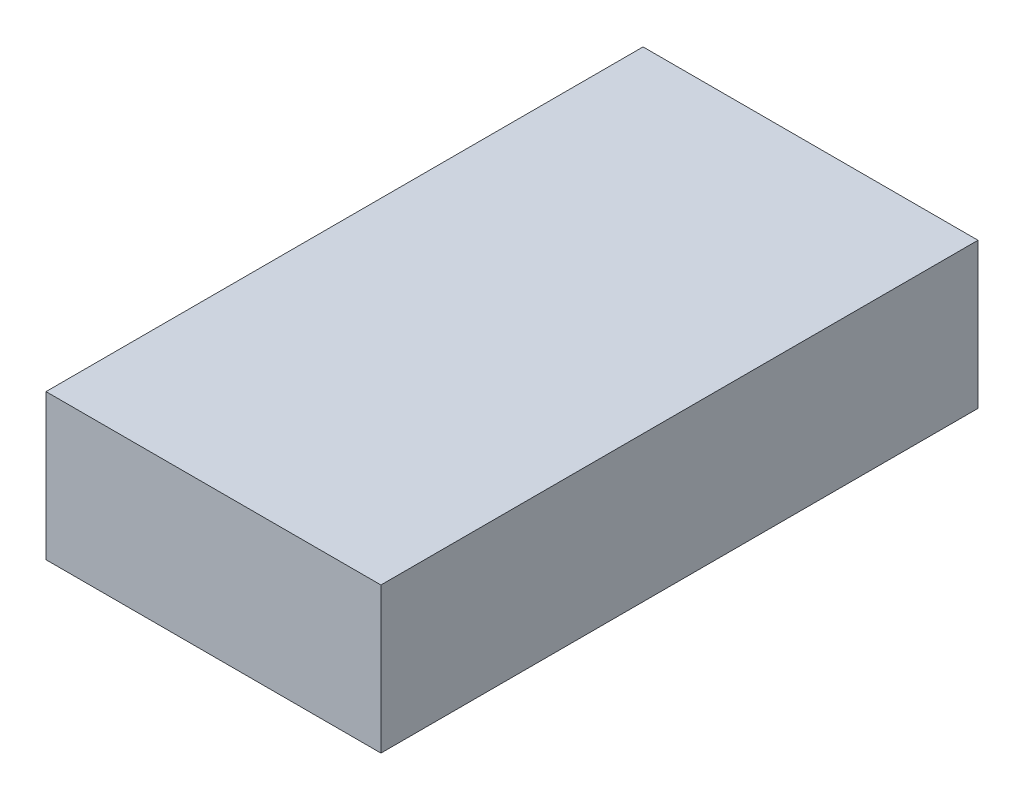
SolidWorks part; units mm, degrees
material "Copper"
ref_plane "Front Plane" through (0, 0, 0) normal (0, 0, 1) x (1, 0, 0)
ref_plane "Top Plane" through (0, 0, 0) normal (0, 1, 0) x (1, 0, 0)
ref_plane "Right Plane" through (0, 0, 0) normal (1, 0, 0) x (0, 0, -1)
sketch "Sketch1" plane through (0, 0, 0) normal (0, 0, 1) x (1, 0, 0)
  line L1 (0, 0) -> (115, 0)
  line L2 (0, 0) -> (0, 50)
  line L3 (0, 50) -> (115, 50)
  line L4 (115, 0) -> (115, 50)
  dimension "D1" = 50
  dimension "D2" = 115
extrude "Boss-Extrude1" add sketch "Sketch1" along normal blind 205
sketch "Sketch2" plane through (0, 0, 0) normal (0, -1, 0) x (1, 0, 0)
  line L0 (9.75, 177.5) -> (104.3481, 177.5) construction
  line L1 (0, 205) -> (115, 205) construction
  line L2 (8.0003, 9.5) -> (104.3481, 9.5) construction
  line L3 (0, 0) -> (115, 0) construction
  line L4 (9.75, 179.5) -> (9.75, 175.5) construction
  line L5 (11.75, 179.5) -> (11.75, 175.5)
  line L6 (7.75, 179.5) -> (7.75, 175.5)
  line L7 (0, 205) -> (0, 0) construction
  line L8 (57.5, 0) -> (57.5, 205) construction
  line L9 (71.2818, 177.5) -> (71.2818, 9.5) construction
  line L11 (105.25, 179.5) -> (105.25, 175.5) construction
  line L12 (103.25, 179.5) -> (103.25, 175.5)
  line L13 (107.25, 179.5) -> (107.25, 175.5)
  line L14 (71.2818, 93.5) -> (7.75, 93.5) construction
  line L15 (9.75, 7.5) -> (9.75, 11.5) construction
  line L16 (11.75, 7.5) -> (11.75, 11.5)
  line L17 (7.75, 7.5) -> (7.75, 11.5)
  line L18 (105.25, 7.5) -> (105.25, 11.5) construction
  line L19 (103.25, 7.5) -> (103.25, 11.5)
  line L20 (107.25, 7.5) -> (107.25, 11.5)
  arc A0 (11.75, 179.5) -> (7.75, 179.5) centre (9.75, 179.5) ccw
  arc A1 (7.75, 175.5) -> (11.75, 175.5) centre (9.75, 175.5) ccw
  arc A2 (103.25, 179.5) -> (107.25, 179.5) centre (105.25, 179.5) cw
  arc A3 (107.25, 175.5) -> (103.25, 175.5) centre (105.25, 175.5) cw
  arc A4 (11.75, 7.5) -> (7.75, 7.5) centre (9.75, 7.5) cw
  arc A5 (7.75, 11.5) -> (11.75, 11.5) centre (9.75, 11.5) cw
  arc A6 (103.25, 7.5) -> (107.25, 7.5) centre (105.25, 7.5) ccw
  arc A7 (107.25, 11.5) -> (103.25, 11.5) centre (105.25, 11.5) ccw
  point P10 (9.75, 177.5)
  point P25 (105.25, 177.5)
  point P32 (9.75, 9.5)
  point P39 (105.25, 9.5)
  dimension "D4" = 2
  dimension "D1" = 27.5
  dimension "D2" = 9.5
  dimension "D3" = 4
  dimension "D5" = 9.75
extrude "Cut-Extrude1" cut sketch "Sketch2" against normal blind 5
